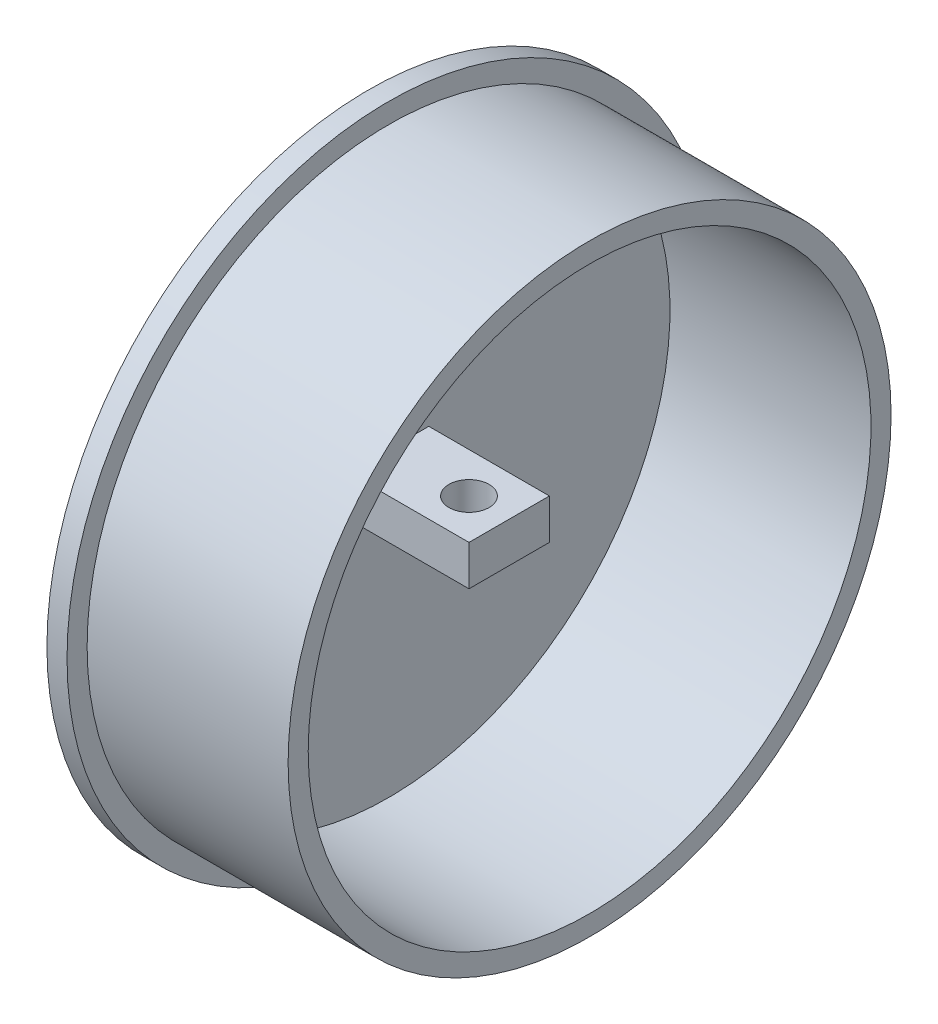
SolidWorks part; units mm, degrees
ref_plane "Ebene vorne" through (0, 0, 0) normal (0, 0, 1) x (1, 0, 0)
ref_plane "Ebene oben" through (0, 0, 0) normal (0, 1, 0) x (1, 0, 0)
ref_plane "Ebene rechts" through (0, 0, 0) normal (1, 0, 0) x (0, 0, -1)
sketch "Skizze1" plane through (0, 0, 0) normal (0, 0, 1) x (1, 0, 0)
  line L0 (0, 0) -> (100, 0) construction
  line L2 (0, 0) -> (-5, 0)
  line L3 (0, 0) -> (0, 80)
  line L4 (0, 80) -> (-5, 80)
  line L5 (-5, 0) -> (-5, 80)
  line L6 (0, 75) -> (50, 75)
  line L7 (0, 75) -> (0, 70)
  line L8 (0, 70) -> (50, 70)
  line L9 (50, 75) -> (50, 70)
  dimension "D1" = 100
  dimension "D2" = 80
  dimension "D3" = 5
  dimension "D4" = 5
  dimension "D5" = 50
  dimension "D6" = 5
revolve "Rotation1" add sketch "Skizze1" angle 360 about L0
sketch "Skizze2" plane through (0, 0, 0) normal (1, 0, 0) x (0, 0, -1)
  line L1 (10, -5) -> (-10, -5)
  line L2 (10, -5) -> (10, 5)
  line L3 (10, 5) -> (-10, 5)
  line L4 (-10, -5) -> (-10, 5)
  line L5 (10, -5) -> (-10, 5) construction
  line L6 (10, 5) -> (-10, -5) construction
  point P0 (0, 0)
  dimension "D1" = 20
  dimension "D2" = 10
extrude "Aufsatz-Linear austragen1" add sketch "Skizze2" along normal blind 30
sketch "Skizze3" plane through (0, -5, 0) normal (0, -1, 0) x (1, 0, 0)
  line L0 (0, -80) -> (0, 80) construction
  circle A0 centre (20, 0) radius 5
  dimension "D1" = 10
  dimension "D2" = 20
extrude "Schnitt-Linear austragen1" cut sketch "Skizze3" against normal blind 30
